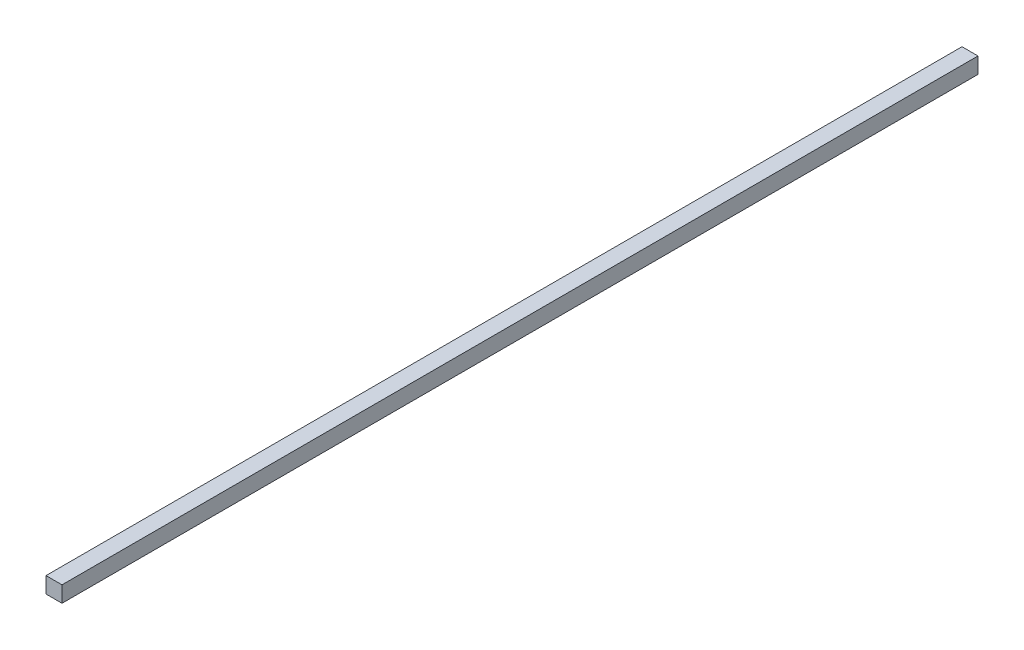
SolidWorks part; units mm, degrees
ref_plane "Front Plane" through (0, 0, 0) normal (0, 0, 1) x (1, 0, 0)
ref_plane "Top Plane" through (0, 0, 0) normal (0, 1, 0) x (1, 0, 0)
ref_plane "Right Plane" through (0, 0, 0) normal (1, 0, 0) x (0, 0, -1)
sketch "Sketch1" plane through (0, 0, 0) normal (0, 0, 1) x (1, 0, 0)
  line L1 (-10, -10) -> (10, -10)
  line L2 (-10, -10) -> (-10, 10)
  line L3 (-10, 10) -> (10, 10)
  line L4 (10, -10) -> (10, 10)
  line L5 (-10, -10) -> (10, 10) construction
  line L6 (-10, 10) -> (10, -10) construction
  point P0 (0, 0)
  dimension "D1" = 20
extrude "Boss-Extrude1" add sketch "Sketch1" along normal blind 1145
